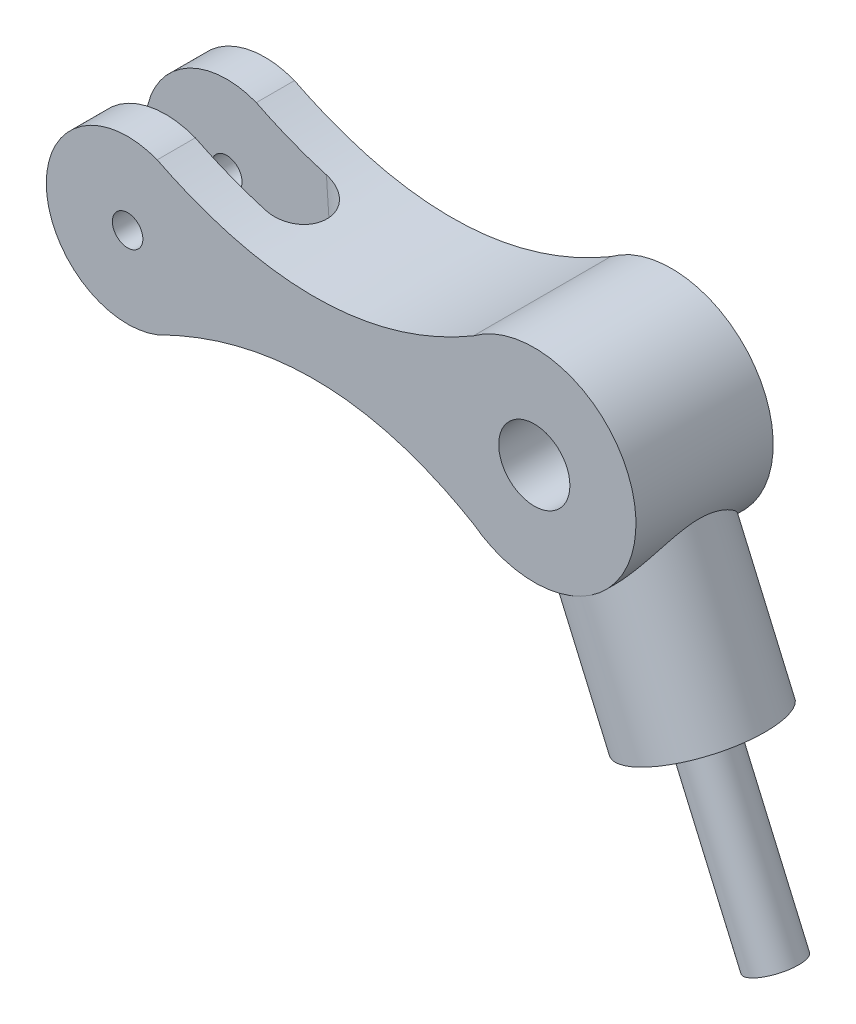
SolidWorks part; units mm, degrees
ref_plane "Front Plane" through (0, 0, 0) normal (0, 0, 1) x (1, 0, 0)
ref_plane "Top Plane" through (0, 0, 0) normal (0, 1, 0) x (1, 0, 0)
ref_plane "Right Plane" through (0, 0, 0) normal (1, 0, 0) x (0, 0, -1)
sketch "Sketch1" plane through (0, 0, 0) normal (0, 0, 1) x (1, 0, 0)
  line L0 (55.9423, 0) -> (15.9423, 0) construction
  circle A0 centre (55.9423, 0) radius 3.5
  arc A1 (49.948, -8.0043) -> (49.948, 8.0043) centre (55.9423, 0) ccw
  circle A2 centre (15.9423, 0) radius 1.5
  arc A3 (18.8512, 7.4524) -> (18.8512, -7.4524) centre (15.9423, 0) ccw
  spline S0 degree 2 poles (49.948, 8.0043) (35.175, -0.7) (18.8512, 7.4524) knots 0 0 0 1 1 1
  spline S1 degree 2 poles (49.948, -8.0043) (35.175, 0.7) (18.8512, -7.4524) knots 0 0 0 1 1 1
extrude "Boss-Extrude2" add sketch "Sketch1" along normal blind 13.5
ref_plane "Plane2" through (-0.424, 6.116, 0) normal (-0.0692, 0.9976, 0) x (0.9976, 0.0692, 0)
sketch "Sketch3" plane through (-0.424, 6.116, 0) normal (-0.0692, 0.9976, 0) x (0.9976, 0.0692, 0)
  line L9 (26.0118, -9.75) -> (7.9041, -9.75)
  line L10 (7.9041, 0) -> (7.9041, -13.5) construction
  line L11 (26.0118, -3.75) -> (7.9041, -3.75)
  line L12 (7.9041, -3.75) -> (7.9041, -9.75)
  arc A1 (26.0118, -9.75) -> (26.0118, -3.75) centre (26.0118, -6.75) ccw
extrude "Cut-Extrude4" cut sketch "Sketch3" against normal through all both and the other way through all
ref_plane "Plane3" through (0, 10, 0) normal (0, 1, 0) x (1, 0, 0)
ref_plane "Plane4" through (12.8824, -29.6274, 0) normal (0.3987, -0.9171, 0) x (0, 0, -1)
sketch "Sketch4" plane through (12.8824, -29.6274, 0) normal (0.3987, -0.9171, 0) x (0, 0, -1)
  line L0 (-13.5, 51.958) -> (0, 51.958) construction
  line L1 (-13.5, 61.3024) -> (-13.5, 42.6136) construction
  line L2 (0, 42.6136) -> (0, 61.3024) construction
  circle A0 centre (-6.75, 51.958) radius 6.75
extrude "Boss-Extrude3" add sketch "Sketch4" along normal blind 13 and the other way blind 5
sketch "Sketch7" plane through (18.0661, -41.5492, 0) normal (0.3987, -0.9171, 0) x (0.9171, 0.3987, 0)
  circle A0 centre (51.958, 6.75) radius 0.7
  circle A1 centre (51.958, 6.75) radius 1.5
extrude "Boss-Extrude4" add sketch "Sketch7" along normal blind 10
sketch "Sketch9" plane through (18.0661, -41.5492, 0) normal (0.3987, -0.9171, 0) x (0.9171, 0.3987, 0)
  circle A0 centre (51.958, 6.75) radius 2.5
extrude "Boss-Extrude5" add sketch "Sketch9" along normal blind 18
